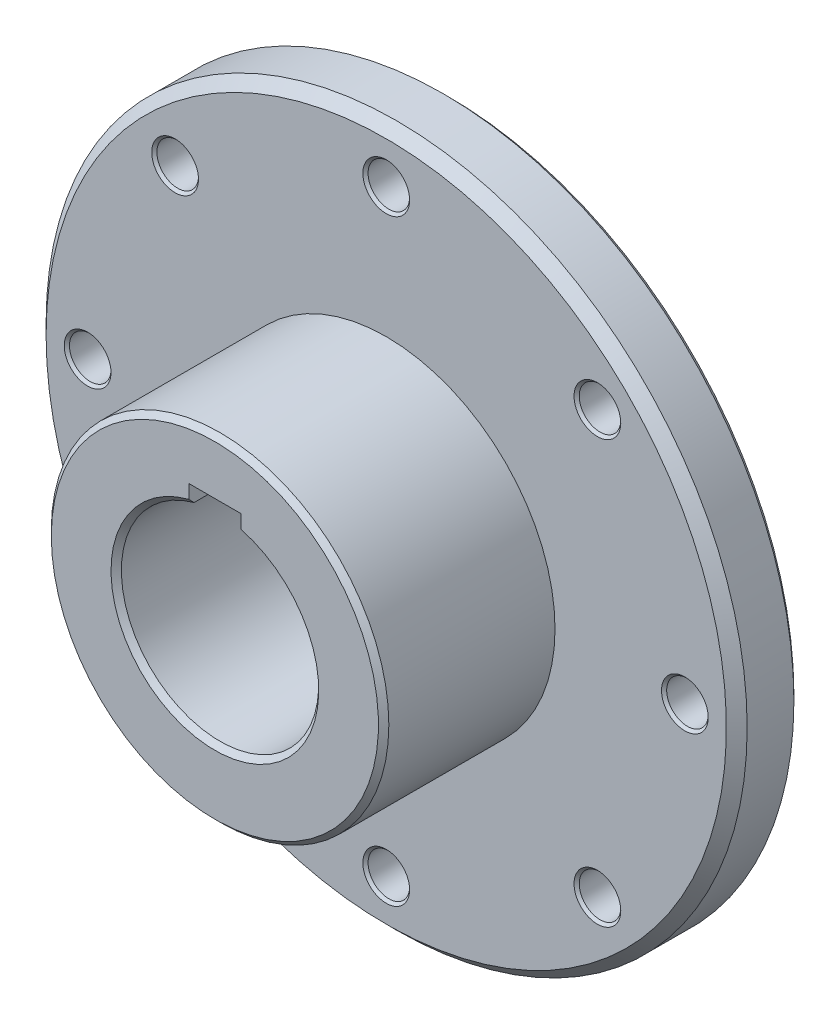
SolidWorks part; units mm, degrees
ref_plane "前视基准面" through (0, 0, 0) normal (0, 0, 1) x (1, 0, 0)
ref_plane "上视基准面" through (0, 0, 0) normal (0, 1, 0) x (1, 0, 0)
ref_plane "右视基准面" through (0, 0, 0) normal (1, 0, 0) x (0, 0, -1)
sketch "草图1" plane through (0, 0, 0) normal (0, 0, 1) x (1, 0, 0)
  circle A0 centre (0, 0) radius 32.5
extrude "拉伸1" add sketch "草图1" along normal blind 10
sketch "草图2" plane through (0, 0, 10) normal (0, 0, 1) x (1, 0, 0)
  circle A0 centre (0, 0) radius 67.5
  dimension "D1" = 135
extrude "拉伸2" add sketch "草图2" along normal blind 12
sketch "草图3" plane through (0, 0, 22) normal (0, 0, 1) x (1, 0, 0)
  circle A0 centre (0, 0) radius 19
extrude "切除-拉伸1" cut sketch "草图3" against normal blind 45
sketch "草图4" plane through (0, 0, 22) normal (0, 0, 1) x (1, 0, 0)
  circle A0 centre (0, 0) radius 32.5
  circle A1 centre (0, 0) radius 19
  dimension "D1" = 65
extrude "拉伸3" add sketch "草图4" along normal blind 33
sketch "草图5" plane through (0, 0, 0) normal (0, 0, -1) x (-1, 0, 0)
  line L1 (-5, 22) -> (5, 22)
  line L2 (-5, 22) -> (-5, 12.2084)
  line L3 (-5, 12.2084) -> (5, 12.2084)
  line L4 (5, 22) -> (5, 12.2084)
extrude "切除-拉伸2" cut sketch "草图5" against normal through all
sketch "草图6" plane through (0, 0, 22) normal (0, 0, 1) x (1, 0, 0)
  circle A0 centre (40.6586, 40.6586) radius 4
  circle A1 centre (0, 57.5) radius 4
  circle A2 centre (57.5, 0) radius 4
  circle A3 centre (40.6586, -40.6586) radius 4
  circle A4 centre (0, -57.5) radius 4
  circle A5 centre (-40.6586, -40.6586) radius 4
  circle A6 centre (-57.5, 0) radius 4
  circle A7 centre (-40.6586, 40.6586) radius 4
extrude "切除-拉伸3" cut sketch "草图6" against normal blind 30
chamfer "倒角1" distance 1 angle 45 4 edges at (0, -19, 55) (32.5, 0, 0) (32.5, 0, 55) (67.5, 0, 10)
chamfer "倒角2" distance 0.5 angle 45 16 edges at (-36.6586, 40.6586, 10) (-36.6586, 40.6586, 22) (-53.5, 0, 10) (-53.5, 0, 22) (-36.6586, -40.6586, 10) (-36.6586, -40.6586, 22) (4, -57.5, 10) (4, -57.5, 22) (44.6586, -40.6586, 10) (44.6586, -40.6586, 22) (61.5, 0, 10) (61.5, 0, 22) (4, 57.5, 10) (4, 57.5, 22) (44.6586, 40.6586, 10) (44.6586, 40.6586, 22)
chamfer "倒角3" distance 2 angle 45 1 edges at (67.5, 0, 22)
chamfer "倒角4" distance 1 angle 45 1 edges at (0, -19, 0)
